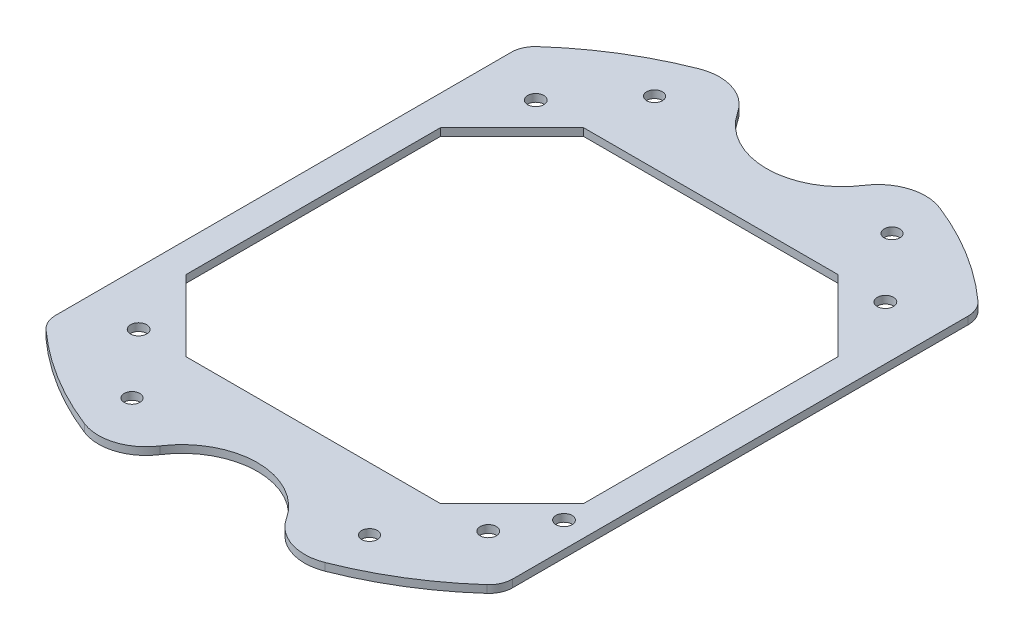
SolidWorks part; units mm, degrees
ref_plane "Front Plane" through (0, 0, 0) normal (0, 0, 1) x (1, 0, 0)
ref_plane "Top Plane" through (0, 0, 0) normal (0, 1, 0) x (1, 0, 0)
ref_plane "Right Plane" through (0, 0, 0) normal (1, 0, 0) x (0, 0, -1)
sketch "Sketch1" plane through (0, 0, 0) normal (0, 1, 0) x (1, 0, 0)
  line L1 (-46.8, -46.8) -> (46.8, -46.8) construction
  line L2 (-46.8, -46.8) -> (-46.8, 46.8)
  line L3 (-46.8, 46.8) -> (46.8, 46.8) construction
  line L4 (46.8, -46.8) -> (46.8, 46.8)
  line L5 (-46.8, -46.8) -> (46.8, 46.8) construction
  line L6 (-46.8, 46.8) -> (46.8, -46.8) construction
  line L8 (-48.0933, -47.9502) -> (-48.0933, 47.9502)
  line L10 (48.0933, -47.9502) -> (48.0933, 47.9502)
  arc A0 (-46.4355, -51.669) -> (-25.3447, -64.6807) centre (0, 0) ccw
  circle A1 centre (69.469, 0) radius 15.875 construction
  arc A2 (13.3113, -60.8189) -> (-13.3113, -60.8189) centre (0, -69.469) ccw
  arc A3 (-13.3113, 60.8189) -> (13.3113, 60.8189) centre (0, 69.469) ccw
  arc A4 (46.4355, 51.669) -> (25.3447, 64.6807) centre (0, 0) ccw
  arc A5 (25.3447, -64.6807) -> (46.4355, -51.669) centre (0, 0) ccw
  arc A6 (-25.3447, 64.6807) -> (-46.4355, 51.669) centre (0, 0) ccw
  arc A7 (13.3113, 60.8189) -> (25.3447, 64.6807) centre (21.6964, 55.3699) cw
  arc A8 (-13.3113, 60.8189) -> (-25.3447, 64.6807) centre (-21.6964, 55.3699) ccw
  arc A9 (13.3113, -60.8189) -> (25.3447, -64.6807) centre (21.6964, -55.3699) ccw
  arc A10 (-13.3113, -60.8189) -> (-25.3447, -64.6807) centre (-21.6964, -55.3699) cw
  arc A11 (-48.0933, 47.9502) -> (-46.4355, 51.669) centre (-43.0933, 47.9502) cw
  arc A12 (48.0933, 47.9502) -> (46.4355, 51.669) centre (43.0933, 47.9502) ccw
  arc A13 (48.0933, -47.9502) -> (46.4355, -51.669) centre (43.0933, -47.9502) cw
  arc A14 (-48.0933, -47.9502) -> (-46.4355, -51.669) centre (-43.0933, -47.9502) ccw
  circle A15 centre (-21.6964, 55.3699) radius 3.61 construction
  point P0 (0, 0)
  point P26 (-15.771, 67.6551)
  point P29 (15.771, -67.6551)
  point P34 (-48.0933, 50.1296)
  point P37 (48.0933, 50.1296)
  point P40 (48.0933, -50.1296)
  point P43 (-48.0933, -50.1296)
  dimension "D3" = 138.938
  dimension "D4" = 31.75
  dimension "D5" = 31.75
  dimension "D6" = 31.75
  dimension "D9" = 10
  dimension "D10" = 5
  dimension "D11" = 7.22
  dimension "D1" = 93.6
  dimension "D2" = 93.6
  dimension "D7" = 100.2592
  dimension "D8" = 100.2592
extrude "Boss-Extrude1" add sketch "Sketch1" against normal blind 1.6 contours A5 A13 L10 A12 A4 A7 A3 A8 A6 A11 L8 A14 A0 A10 A2 A9
hole_wizard "Enclosure Mounting Holes - M3 Clearance Hole1" positions "Sketch4" profile "Sketch5" hole size "M3" standard "ANSI Metric" end condition through all
sketch "Sketch4" plane through (0, 0, 0) normal (0, 1, 0) x (1, 0, 0)
  line L0 (-46.8, -46.8) -> (46.8, -46.8) construction
  line L1 (-46.8, -46.8) -> (-46.8, 46.8) construction
  line L2 (46.8, -46.8) -> (46.8, 46.8) construction
  line L3 (-46.8, 46.8) -> (46.8, 46.8) construction
  point P0 (-36.8, 41.8)
  point P2 (-36.8, -41.8)
  point P4 (36.8, -41.8)
  point P6 (36.8, 41.8)
  dimension "D1" = 5
  dimension "D2" = 10
  dimension "D3" = 10
  dimension "D4" = 5
  dimension "D5" = 10
  dimension "D6" = 5
  dimension "D7" = 5
  dimension "D8" = 10
sketch "Sketch5" plane through (-36.8, 0, -41.8) normal (1, 0, 0) x (0, 0, 1)
  line L0 (0, 0) -> (0, 1.6)
  line L1 (0, 1.6) -> (1.7, 1.6)
  line L2 (1.7, 1.6) -> (1.7, 0)
  line L5 (1.7, 0) -> (0, 0)
  line L11 (0, -6.35) -> (0, 107.95) construction
  dimension "Thru Hole Dia." = 3.4
  dimension "Thru Hole Depth" = 1.6
hole_wizard "Bulkhead Mounting Holes - M4x0.7 Tapped Hole1" positions "Sketch11" profile "Sketch10" tap size "M4x0.7" standard "ANSI Metric" end condition through all
sketch "Sketch11" plane through (0, 0, 0) normal (0, 1, 0) x (1, 0, 0)
  point P0 (-25, 55)
  point P3 (25, 55)
  point P6 (25, -55)
  point P9 (-25, -55)
  dimension "D1" = 55
  dimension "D2" = 25
  dimension "D3" = 25
  dimension "D4" = 55
  dimension "D5" = 55
  dimension "D6" = 25
  dimension "D7" = 25
  dimension "D8" = 55
sketch "Sketch10" plane through (-25, 0, -55) normal (1, 0, 0) x (0, 0, 1)
  line L0 (0, 0) -> (0, 1.6)
  line L1 (0, 1.6) -> (1.65, 1.6)
  line L2 (1.65, 1.6) -> (1.65, 0)
  line L5 (1.65, 0) -> (0, 0)
  line L11 (0, -6.35) -> (0, 107.95) construction
  dimension "Thru Tap Drill Dia." = 3.3
  dimension "Thru Tap Drill Depth" = 1.6
cosmetic thread "Hole Thread1" parameters "D2"=4
cosmetic thread "Hole Thread2" parameters "D2"=4
cosmetic thread "Hole Thread3" parameters "D2"=4
cosmetic thread "Hole Thread4" parameters "D2"=4
sketch "Sketch14" plane through (0, 0, 0) normal (0, 1, 0) x (1, 0, 0)
  line L0 (46.8, -46.8) -> (46.8, 46.8) construction
  line L1 (-46.8, -46.8) -> (46.8, -46.8) construction
  circle A0 centre (42.75, -31.8) radius 1.7
  dimension "D1" = 4.05
  dimension "D3" = 3.4
  dimension "D2" = 15
extrude "Cut-Extrude1" cut sketch "Sketch14" against normal through all contours A0
sketch "Sketch15" plane through (0, 0, 0) normal (0, 1, 0) x (1, 0, 0)
  line L0 (-1.1382, 6.3003) -> (-26.1448, 34.8691)
  line L8 (-5.8423, -0.9786) -> (-29.5197, -28.4852)
  line L9 (-32.1565, -27.5066) -> (-32.1565, 27.5066)
  line L10 (-32.1565, -37.3571) -> (32.1565, -37.3571)
  line L11 (-32.1565, -37.3571) -> (-32.1565, 37.3571)
  line L12 (-32.1565, 37.3571) -> (32.1565, 37.3571)
  line L13 (32.1565, -37.3571) -> (32.1565, 37.3571)
  line L14 (-32.1565, -37.3571) -> (32.1565, 37.3571) construction
  line L15 (-32.1565, 37.3571) -> (32.1565, -37.3571) construction
  line L16 (1.1274, 6.3097) -> (25.719, 34.8785)
  line L17 (24.5822, 37.3571) -> (-25.0161, 37.3571)
  line L18 (-32.1565, 0) -> (32.1565, 0) construction
  line L19 (24.5822, -37.3571) -> (-25.0161, -37.3571)
  line L20 (1.1274, -6.3097) -> (25.719, -34.8785)
  line L21 (-1.1382, -6.3003) -> (-26.1448, -34.8691)
  line L22 (-5.8423, 0.9786) -> (-29.5197, 28.4852)
  line L23 (0, 25) -> (0, -25) construction
  line L24 (32.1565, -27.5066) -> (32.1565, 27.5066)
  line L25 (5.8423, 0.9786) -> (29.5197, 28.4852)
  line L26 (5.8423, -0.9786) -> (29.5197, -28.4852)
  arc A0 (-26.1448, 34.8691) -> (-25.0161, 37.3571) centre (-25.0161, 35.8571) cw
  arc A1 (-1.1382, 6.3003) -> (1.1274, 6.3097) centre (-0.0095, 7.2883) ccw
  arc A2 (25.719, 34.8785) -> (24.5822, 37.3571) centre (24.5822, 35.8571) ccw
  arc A3 (32.1565, 27.5066) -> (29.5197, 28.4852) centre (30.6565, 27.5066) ccw
  arc A4 (32.1565, -27.5066) -> (29.5197, -28.4852) centre (30.6565, -27.5066) cw
  arc A5 (5.8423, 0.9786) -> (5.8423, -0.9786) centre (6.9792, 0) ccw
  arc A6 (1.1274, -6.3097) -> (-1.1382, -6.3003) centre (-0.0095, -7.2883) ccw
  arc A7 (24.5822, -37.3571) -> (25.719, -34.8785) centre (24.5822, -35.8571) ccw
  arc A8 (-25.0161, -37.3571) -> (-26.1448, -34.8691) centre (-25.0161, -35.8571) cw
  arc A9 (-5.8423, 0.9786) -> (-5.8423, -0.9786) centre (-6.9792, 0) cw
  arc A10 (-29.5197, -28.4852) -> (-32.1565, -27.5066) centre (-30.6565, -27.5066) cw
  arc A11 (-29.5197, 28.4852) -> (-32.1565, 27.5066) centre (-30.6565, 27.5066) ccw
  point P0 (0, 0)
  point P5 (0, 0)
  point P27 (-28.3226, 37.3571)
  point P30 (0, 5)
  point P33 (27.8526, 37.3571)
  point P36 (32.1565, 31.5485)
  point P39 (32.1565, -31.5485)
  point P42 (5, 0)
  point P45 (0, -5)
  point P48 (27.8526, -37.3571)
  point P51 (-28.3226, -37.3571)
  point P54 (-5, 0)
  point P57 (-32.1565, -31.5485)
  point P60 (-32.1565, 31.5485)
  dimension "D9" = 1.5
  dimension "D1" = 5
  dimension "D2" = 5
  dimension "D3" = 32.3571
  dimension "D4" = 81.917
  dimension "D5" = 42.6936
  dimension "D6" = 64.313
  dimension "D7" = 32.1565
  dimension "D8" = 5
extrude "Cut-Extrude2" [suppressed] cut sketch "Sketch15" against normal blind 10 contours L8 L22 L9 | L0 L16 L12 | L25 L26 L13 | L20 L21 L10
ref_plane "Plane1" through (0, 0, 0) normal (-1, 0, 0) x (0, 0, 1)
sketch "Sketch17" plane through (0, 0, 0) normal (0, 1, 0) x (1, 0, 0)
  line L0 (26.8, -41.8) -> (41.8, -26.8)
  line L1 (-26.8, -41.8) -> (26.8, -41.8)
  line L2 (-41.8, -26.8) -> (-41.8, 26.8)
  line L3 (-26.8, 41.8) -> (26.8, 41.8)
  line L4 (41.8, -26.8) -> (41.8, 26.8)
  line L5 (-41.8, -41.8) -> (41.8, 41.8) construction
  line L6 (-41.8, 41.8) -> (41.8, -41.8) construction
  line L7 (41.8, 26.8) -> (26.8, 41.8)
  line L8 (-41.8, 26.8) -> (-26.8, 41.8)
  line L9 (-26.8, -41.8) -> (-41.8, -26.8)
  point P0 (0, 0)
  dimension "D1" = 83.6
  dimension "D2" = 83.6
extrude "Cut-Extrude3" cut sketch "Sketch17" against normal blind 10 contours L9 L1 L0 L4 L7 L3 L8 L2
